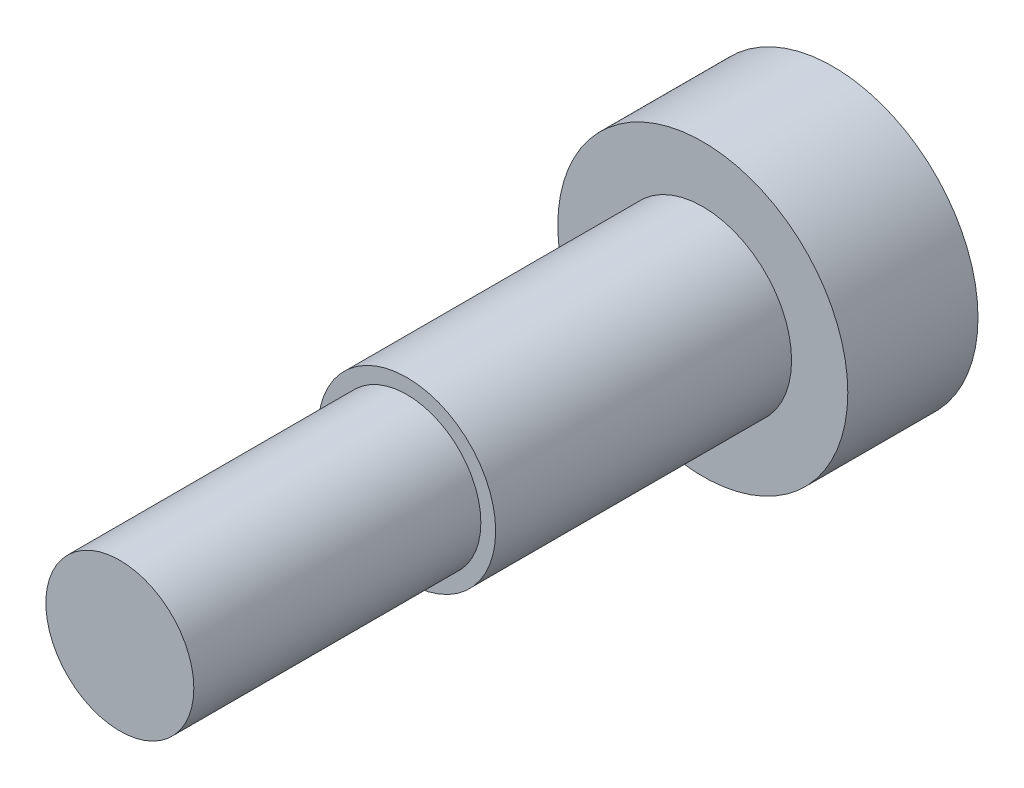
SolidWorks part; units mm, degrees
ref_plane "前视基准面" through (0, 0, 0) normal (0, 0, 1) x (1, 0, 0)
ref_plane "上视基准面" through (0, 0, 0) normal (0, 1, 0) x (1, 0, 0)
ref_plane "右视基准面" through (0, 0, 0) normal (1, 0, 0) x (0, 0, -1)
sketch "草图1" plane through (0, 0, 0) normal (0, 0, 1) x (1, 0, 0)
  circle A0 centre (0, 0) radius 4.9
  dimension "D1" = 9.8
extrude "凸台-拉伸1" add sketch "草图1" along normal blind 4.4
sketch "草图2" plane through (0, 0, 4.4) normal (0, 0, 1) x (1, 0, 0)
  circle A0 centre (0, 0) radius 3
  dimension "D1" = 6
extrude "凸台-拉伸2" add sketch "草图2" along normal blind 10
sketch "草图3" plane through (0, 0, 14.4) normal (0, 0, 1) x (1, 0, 0)
  circle A0 centre (0, 0) radius 2.5
  dimension "D1" = 5
extrude "凸台-拉伸3" add sketch "草图3" along normal blind 9.7
sketch "草图4" plane through (0, 0, 0) normal (0, 0, -1) x (-1, 0, 0)
  line L1 (0, 1.7321) -> (-1.5, 0.866)
  line L2 (-1.5, 0.866) -> (-1.5, -0.866)
  line L3 (-1.5, -0.866) -> (0, -1.7321)
  line L4 (0, -1.7321) -> (1.5, -0.866)
  line L5 (1.5, -0.866) -> (1.5, 0.866)
  line L6 (1.5, 0.866) -> (0, 1.7321)
  circle A0 centre (0, 0) radius 1.5 construction
  dimension "D1" = 3
extrude "切除-拉伸1" cut sketch "草图4" against normal blind 2
